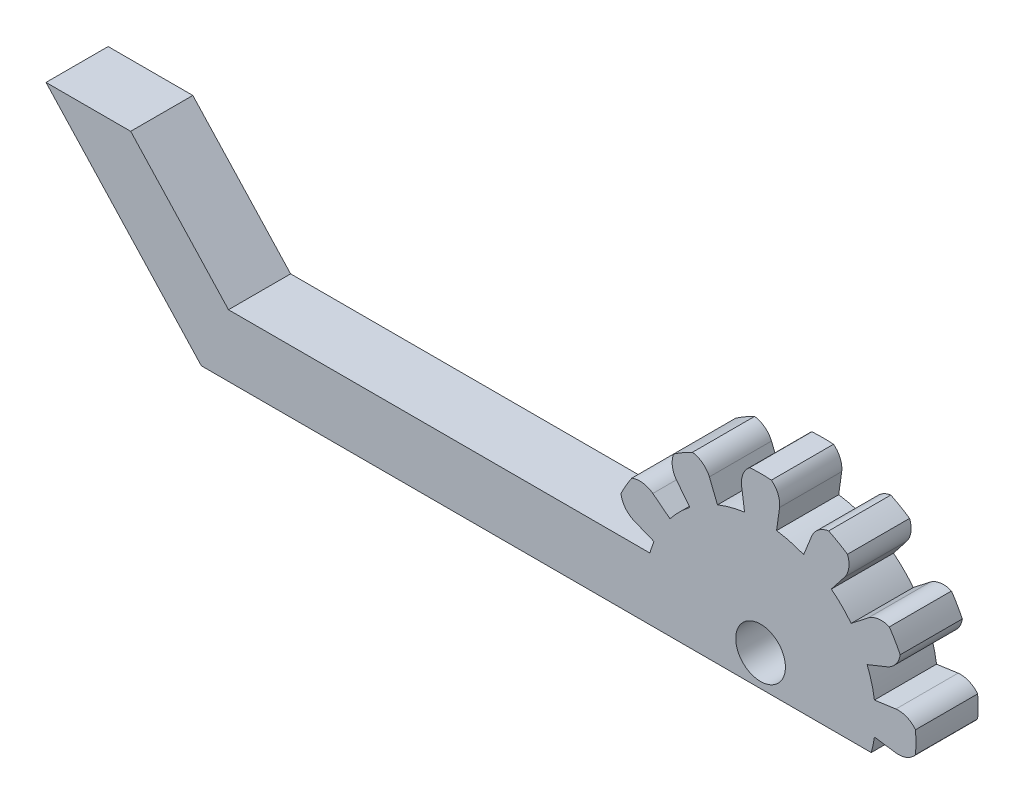
SolidWorks part; units mm, degrees
ref_plane "Ön Düzlem" through (0, 0, 0) normal (0, 0, 1) x (1, 0, 0)
ref_plane "Üst Düzlem" through (0, 0, 0) normal (0, 1, 0) x (1, 0, 0)
ref_plane "Sağ Düzlem" through (0, 0, 0) normal (1, 0, 0) x (0, 0, -1)
sketch "Sketch1" plane through (0, 0, 0) normal (0, 0, 1) x (1, 0, 0)
  line L0 (0, 0) -> (0, -15) construction
  line L1 (0, -15) -> (0, -22) construction
  line L2 (0, -22) -> (0, -25) construction
  line L3 (0, 0) -> (-3.4793, -24.7567) construction
  line L4 (0, 0) -> (-6.8909, -24.0315) construction
  line L5 (0, 0) -> (-1.7439, -24.9391) construction
  line L6 (-115, 22) -> (-101.3716, 22)
  line L7 (-101.3716, 22) -> (-101.2588, 21.9409)
  line L8 (0, 0) -> (-3.0618, -21.7859) construction
  line L9 (0, 0) -> (-1.7439, -24.9391) construction
  line L12 (0, 0) -> (-2.5747, -18.32) construction
  line L13 (-2.5747, -18.32) -> (-3.0618, -21.7859)
  line L14 (2.5747, -18.32) -> (3.0618, -21.7859)
  line L18 (-11.3897, -14.5782) -> (-13.5446, -17.3362)
  line L19 (-6.9302, -17.1529) -> (-8.2413, -20.398)
  line L22 (-17.1529, -6.9302) -> (-20.398, -8.2413)
  line L23 (-14.5782, -11.3897) -> (-17.3362, -13.5446)
  line L26 (-18.32, 2.5747) -> (-21.7859, 3.0618)
  line L27 (-18.32, -2.5747) -> (-21.7859, -3.0618)
  line L30 (-14.5782, 11.3897) -> (-17.3362, 13.5446)
  line L31 (-17.1529, 6.9302) -> (-20.398, 8.2413)
  line L34 (-6.9302, 17.1529) -> (-8.2413, 20.398)
  line L35 (-11.3897, 14.5782) -> (-13.5446, 17.3362)
  line L38 (2.5747, 18.32) -> (3.0618, 21.7859)
  line L39 (-2.5747, 18.32) -> (-3.0618, 21.7859)
  line L42 (11.3897, 14.5782) -> (13.5446, 17.3362)
  line L43 (6.9302, 17.1529) -> (8.2413, 20.398)
  line L46 (17.1529, 6.9302) -> (20.398, 8.2413)
  line L47 (14.5782, 11.3897) -> (17.3362, 13.5446)
  line L50 (18.32, -2.5747) -> (21.7859, -3.0618)
  line L51 (18.32, 2.5747) -> (21.7859, 3.0618)
  line L54 (14.5782, -11.3897) -> (17.3362, -13.5446)
  line L55 (17.1529, -6.9302) -> (20.398, -8.2413)
  line L58 (6.9302, -17.1529) -> (8.2413, -20.398)
  line L59 (11.3897, -14.5782) -> (13.5446, -17.3362)
  line L69 (0, 5) -> (0, -5) construction
  line L70 (0, -5) -> (-90, -5)
  line L74 (0, 0) -> (0, 30.6961) construction
  line L75 (0, 22) -> (-115, 22) construction
  line L76 (-90, -5) -> (-115, 22)
  line L77 (-85.6308, 5) -> (-101.3716, 22)
  line L78 (0, 5) -> (-85.6308, 5)
  line L80 (0, -5) -> (17.8115, -5)
  circle A0 centre (0, 0) radius 25 construction
  circle A1 centre (0, 0) radius 15 construction
  circle A2 centre (0, 0) radius 22 construction
  circle A3 centre (0, 0) radius 18.5 construction
  arc A4 (0, -18.5) -> (-2.5747, -18.32) centre (0, 0) ccw
  arc A5 (-1.7439, -24.9391) -> (-3.0618, -21.7859) centre (0.4276, -22.1795) cw
  arc A6 (-1.7439, -24.9391) -> (1.7439, -24.9391) centre (0, 0) ccw
  arc A7 (1.7439, -24.9391) -> (3.0618, -21.7859) centre (-0.4276, -22.1795) ccw
  arc A8 (0, -18.5) -> (2.5747, -18.32) centre (0, 0) cw
  arc A9 (-9.25, -16.0215) -> (-6.9302, -17.1529) centre (0, 0) cw
  arc A10 (-9.25, -16.0215) -> (-11.3897, -14.5782) centre (0, 0) ccw
  arc A11 (-10.9593, -22.4699) -> (-8.2413, -20.398) centre (-11.4601, -18.9942) ccw
  arc A12 (-13.9798, -20.7259) -> (-13.5446, -17.3362) centre (-10.7194, -19.4218) cw
  arc A13 (-13.9798, -20.7259) -> (-10.9593, -22.4699) centre (0, 0) ccw
  arc A14 (-16.0215, -9.25) -> (-14.5782, -11.3897) centre (0, 0) cw
  arc A15 (-16.0215, -9.25) -> (-17.1529, -6.9302) centre (0, 0) ccw
  arc A16 (-20.7259, -13.9798) -> (-17.3362, -13.5446) centre (-19.4218, -10.7194) ccw
  arc A17 (-22.4699, -10.9593) -> (-20.398, -8.2413) centre (-18.9942, -11.4601) cw
  arc A18 (-22.4699, -10.9593) -> (-20.7259, -13.9798) centre (0, 0) ccw
  arc A19 (-18.5, 0) -> (-18.32, -2.5747) centre (0, 0) cw
  arc A20 (-18.5, 0) -> (-18.32, 2.5747) centre (0, 0) ccw
  arc A21 (-24.9391, -1.7439) -> (-21.7859, -3.0618) centre (-22.1795, 0.4276) ccw
  arc A22 (-24.9391, 1.7439) -> (-21.7859, 3.0618) centre (-22.1795, -0.4276) cw
  arc A23 (-24.9391, 1.7439) -> (-24.9391, -1.7439) centre (0, 0) ccw
  arc A24 (-16.0215, 9.25) -> (-17.1529, 6.9302) centre (0, 0) cw
  arc A25 (-16.0215, 9.25) -> (-14.5782, 11.3897) centre (0, 0) ccw
  arc A26 (-22.4699, 10.9593) -> (-20.398, 8.2413) centre (-18.9942, 11.4601) ccw
  arc A27 (-20.7259, 13.9798) -> (-17.3362, 13.5446) centre (-19.4218, 10.7194) cw
  arc A28 (-20.7259, 13.9798) -> (-22.4699, 10.9593) centre (0, 0) ccw
  arc A29 (-9.25, 16.0215) -> (-11.3897, 14.5782) centre (0, 0) cw
  arc A30 (-9.25, 16.0215) -> (-6.9302, 17.1529) centre (0, 0) ccw
  arc A31 (-13.9798, 20.7259) -> (-13.5446, 17.3362) centre (-10.7194, 19.4218) ccw
  arc A32 (-10.9593, 22.4699) -> (-8.2413, 20.398) centre (-11.4601, 18.9942) cw
  arc A33 (-10.9593, 22.4699) -> (-13.9798, 20.7259) centre (0, 0) ccw
  arc A34 (0, 18.5) -> (-2.5747, 18.32) centre (0, 0) cw
  arc A35 (0, 18.5) -> (2.5747, 18.32) centre (0, 0) ccw
  arc A36 (-1.7439, 24.9391) -> (-3.0618, 21.7859) centre (0.4276, 22.1795) ccw
  arc A37 (1.7439, 24.9391) -> (3.0618, 21.7859) centre (-0.4276, 22.1795) cw
  arc A38 (1.7439, 24.9391) -> (-1.7439, 24.9391) centre (0, 0) ccw
  arc A39 (9.25, 16.0215) -> (6.9302, 17.1529) centre (0, 0) cw
  arc A40 (9.25, 16.0215) -> (11.3897, 14.5782) centre (0, 0) ccw
  arc A41 (10.9593, 22.4699) -> (8.2413, 20.398) centre (11.4601, 18.9942) ccw
  arc A42 (13.9798, 20.7259) -> (13.5446, 17.3362) centre (10.7194, 19.4218) cw
  arc A43 (13.9798, 20.7259) -> (10.9593, 22.4699) centre (0, 0) ccw
  arc A44 (16.0215, 9.25) -> (14.5782, 11.3897) centre (0, 0) cw
  arc A45 (16.0215, 9.25) -> (17.1529, 6.9302) centre (0, 0) ccw
  arc A46 (20.7259, 13.9798) -> (17.3362, 13.5446) centre (19.4218, 10.7194) ccw
  arc A47 (22.4699, 10.9593) -> (20.398, 8.2413) centre (18.9942, 11.4601) cw
  arc A48 (22.4699, 10.9593) -> (20.7259, 13.9798) centre (0, 0) ccw
  arc A49 (18.5, 0) -> (18.32, 2.5747) centre (0, 0) cw
  arc A50 (18.5, 0) -> (18.32, -2.5747) centre (0, 0) ccw
  arc A51 (24.9391, 1.7439) -> (21.7859, 3.0618) centre (22.1795, -0.4276) ccw
  arc A52 (24.9391, -1.7439) -> (21.7859, -3.0618) centre (22.1795, 0.4276) cw
  arc A53 (24.9391, -1.7439) -> (24.9391, 1.7439) centre (0, 0) ccw
  arc A54 (16.0215, -9.25) -> (17.1529, -6.9302) centre (0, 0) cw
  arc A55 (16.0215, -9.25) -> (14.5782, -11.3897) centre (0, 0) ccw
  arc A56 (22.4699, -10.9593) -> (20.398, -8.2413) centre (18.9942, -11.4601) ccw
  arc A57 (20.7259, -13.9798) -> (17.3362, -13.5446) centre (19.4218, -10.7194) cw
  arc A58 (20.7259, -13.9798) -> (22.4699, -10.9593) centre (0, 0) ccw
  arc A59 (9.25, -16.0215) -> (11.3897, -14.5782) centre (0, 0) cw
  arc A60 (9.25, -16.0215) -> (6.9302, -17.1529) centre (0, 0) ccw
  arc A61 (13.9798, -20.7259) -> (13.5446, -17.3362) centre (10.7194, -19.4218) ccw
  arc A62 (10.9593, -22.4699) -> (8.2413, -20.398) centre (11.4601, -18.9942) cw
  arc A63 (10.9593, -22.4699) -> (13.9798, -20.7259) centre (0, 0) ccw
  circle A64 centre (0, 0) radius 18.5
  circle A131 centre (0, 0) radius 4
  point P138 (0, 0)
  dimension "D1" = 44
  dimension "D2" = 30
  dimension "D3" = 50
  dimension "D7" = 37
  dimension "D8" = 3.5115
  dimension "D20" = 8
  dimension "D4" = 8
  dimension "D5" = 8
  dimension "D6" = 4
  dimension "D24" = 0
  dimension "D25" = 10
  dimension "D26" = 5
  dimension "D27" = 90
  dimension "D29" = 115
  dimension "D30" = 10
  dimension "D9" = 12
extrude "Boss-Extrude2" add sketch "Sketch1" along normal blind 10
